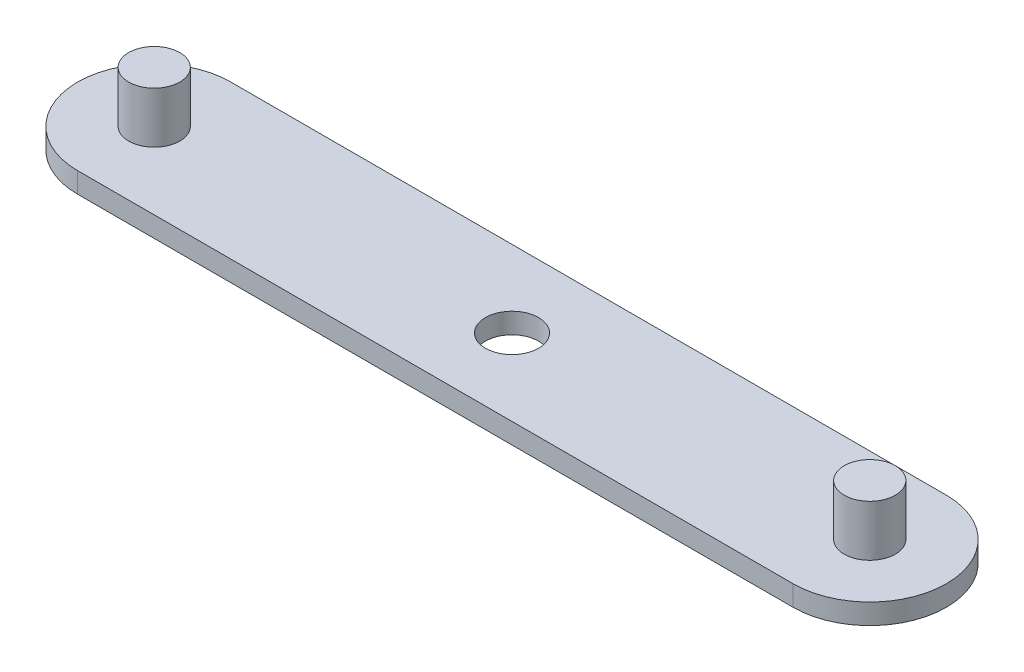
SolidWorks part; units mm, degrees
ref_plane "Front Plane" through (0, 0, 0) normal (0, 0, 1) x (1, 0, 0)
ref_plane "Top Plane" through (0, 0, 0) normal (0, 1, 0) x (1, 0, 0)
ref_plane "Right Plane" through (0, 0, 0) normal (1, 0, 0) x (0, 0, -1)
sketch "Sketch1" plane through (0, 0, 0) normal (0, 1, 0) x (1, 0, 0)
  line L1 (-44.45, -9.525) -> (44.45, -9.525)
  line L2 (-44.45, -9.525) -> (-44.45, 9.525)
  line L3 (-44.45, 9.525) -> (44.45, 9.525)
  line L4 (44.45, -9.525) -> (44.45, 9.525)
  line L5 (-44.45, -9.525) -> (44.45, 9.525) construction
  line L6 (-44.45, 9.525) -> (44.45, -9.525) construction
  arc A0 (-44.45, -9.525) -> (-44.45, 9.525) centre (-44.45, 0) cw
  arc A1 (44.45, 9.525) -> (44.45, -9.525) centre (44.45, 0) cw
  point P0 (0, 0)
  dimension "D1" = 19.05
  dimension "D2" = 88.9
extrude "Boss-Extrude1" add sketch "Sketch1" along normal blind 2.54 contours A0 L2 | L1 L4 L3 L2 | A1 L4
sketch "Sketch2" plane through (0, 2.54, 0) normal (0, 1, 0) x (1, 0, 0)
  circle A0 centre (-44.45, 0) radius 3.175
  arc A1 (-44.45, 9.525) -> (-44.45, -9.525) centre (-44.45, 0) ccw construction
  circle A2 centre (44.45, 0) radius 3.175
  arc A3 (44.45, -9.525) -> (44.45, 9.525) centre (44.45, 0) ccw construction
  dimension "D1" = 6.35
extrude "Boss-Extrude2" add sketch "Sketch2" along normal blind 6.35
sketch "Sketch3" plane through (0, 2.54, 0) normal (0, 1, 0) x (1, 0, 0)
  circle A0 centre (0, 0) radius 3.302
  dimension "D1" = 6.604
extrude "Cut-Extrude1" cut sketch "Sketch3" against normal up to next
